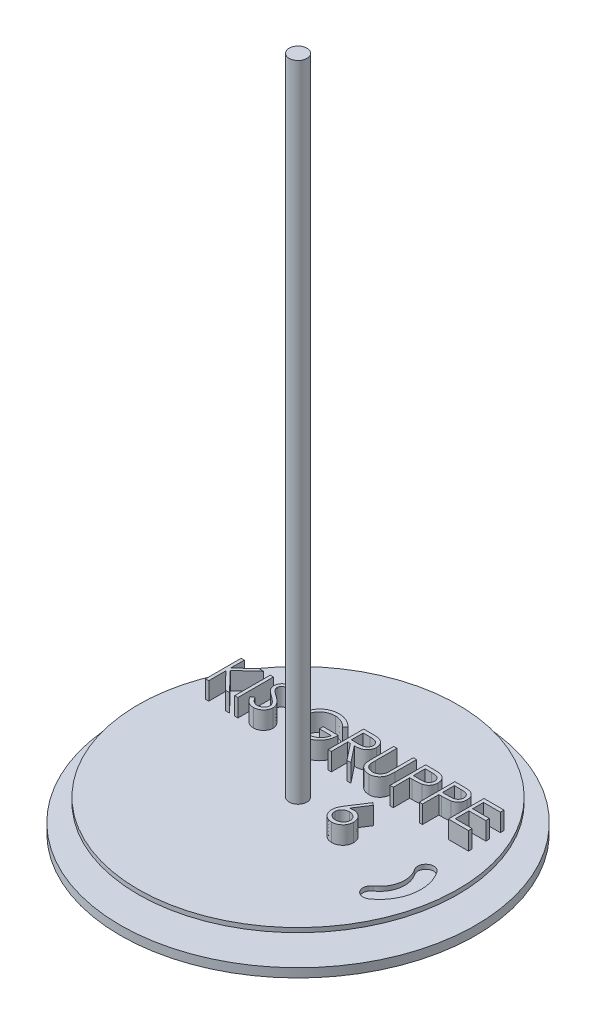
SolidWorks part; units mm, degrees
ref_plane "Front Plane" through (0, 0, 0) normal (0, 0, 1) x (1, 0, 0)
ref_plane "Top Plane" through (0, 0, 0) normal (0, 1, 0) x (1, 0, 0)
ref_plane "Right Plane" through (0, 0, 0) normal (1, 0, 0) x (0, 0, -1)
sketch "Sketch1" plane through (0, 0, 0) normal (0, 1, 0) x (1, 0, 0)
  circle A0 centre (0, 0) radius 200
  dimension "D1" = 400
extrude "Boss-Extrude1" add sketch "Sketch1" along normal blind 10
sketch "Sketch2" plane through (0, 10, 0) normal (0, 1, 0) x (1, 0, 0)
  circle A0 centre (0, 0) radius 10
  dimension "D1" = 20
extrude "Boss-Extrude2" add sketch "Sketch2" along normal blind 750
ref_plane "Plane1" through (0, 30, 0) normal (0, 1, 0) x (1, 0, 0)
sketch "Sketch3" plane through (0, 30, 0) normal (0, 1, 0) x (1, 0, 0)
  circle A0 centre (0, 0) radius 180
  dimension "D1" = 360
extrude "Boss-Extrude3" add sketch "Sketch3" along normal blind 5
sketch "Sketch4" plane through (0, 35, 0) normal (0, 1, 0) x (1, 0, 0)
  arc A0 (143.7707, 0) -> (134.0371, -51.8911) centre (112.9583, -21.0787) cw construction
  arc A1 (139.1562, -59.3741) -> (151.2537, 5.1191) centre (112.9583, -21.0787) ccw
  arc A2 (128.9179, -44.4081) -> (136.2877, -5.1191) centre (112.9583, -21.0787) ccw
  arc A3 (128.9179, -44.4081) -> (139.1562, -59.3741) centre (134.0371, -51.8911) ccw
  arc A4 (151.2537, 5.1191) -> (136.2877, -5.1191) centre (143.7707, 0) ccw
  point P3 (149.6509, -27.9615)
extrude "Cut-Extrude1" cut sketch "Sketch4" against normal up to next
sketch "Sketch7" plane through (0, 35, 0) normal (0, 1, 0) x (1, 0, 0)
  text T0 "KIS GRUPPE \r\n             6\r\n" font "Century Gothic" height 40
extrude "Boss-Extrude5" add sketch "Sketch7" along normal blind 20
